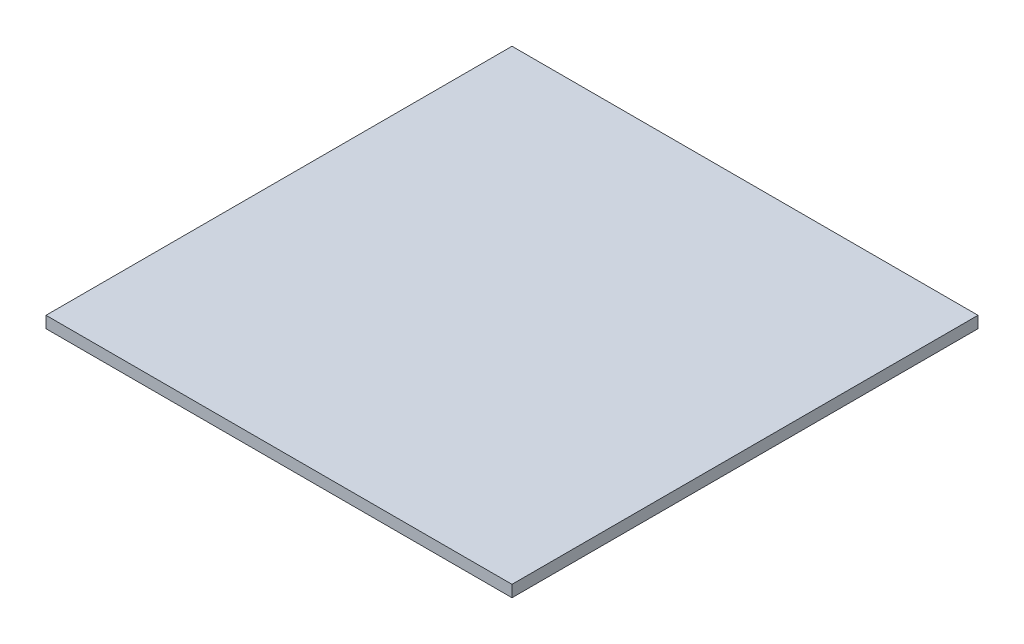
SolidWorks part; units mm, degrees
ref_plane "前视基准面" through (0, 0, 0) normal (0, 0, 1) x (1, 0, 0)
ref_plane "上视基准面" through (0, 0, 0) normal (0, 1, 0) x (1, 0, 0)
ref_plane "右视基准面" through (0, 0, 0) normal (1, 0, 0) x (0, 0, -1)
sketch "草图1" plane through (0, 0, 0) normal (0, 1, 0) x (1, 0, 0)
  line L1 (-500, -500) -> (500, -500)
  line L2 (-500, -500) -> (-500, 500)
  line L3 (-500, 500) -> (500, 500)
  line L4 (500, -500) -> (500, 500)
  line L5 (-500, -500) -> (500, 500) construction
  line L6 (-500, 500) -> (500, -500) construction
  point P0 (0, 0)
  dimension "D1" = 1000
  dimension "D2" = 1000
extrude "凸台-拉伸1" add sketch "草图1" along normal blind 25
